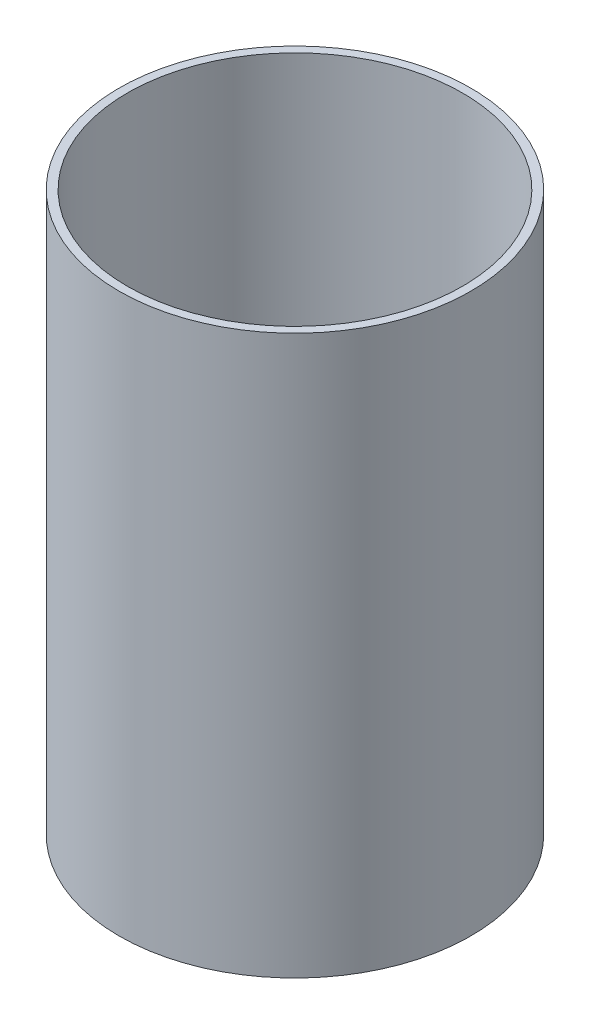
SolidWorks part; units mm, degrees
ref_plane "Plan de face" through (0, 0, 0) normal (0, 0, 1) x (1, 0, 0)
ref_plane "Plan de dessus" through (0, 0, 0) normal (0, 1, 0) x (1, 0, 0)
ref_plane "Plan de droite" through (0, 0, 0) normal (1, 0, 0) x (0, 0, -1)
sketch "Esquisse1" plane through (0, 0, 0) normal (0, 1, 0) x (1, 0, 0)
  circle A0 centre (0, 0) radius 31.5
  circle A1 centre (0, 0) radius 30
  dimension "D1" = 63
  dimension "D2" = 60
extrude "Boss.-Extru.1" add sketch "Esquisse1" along normal blind 100
